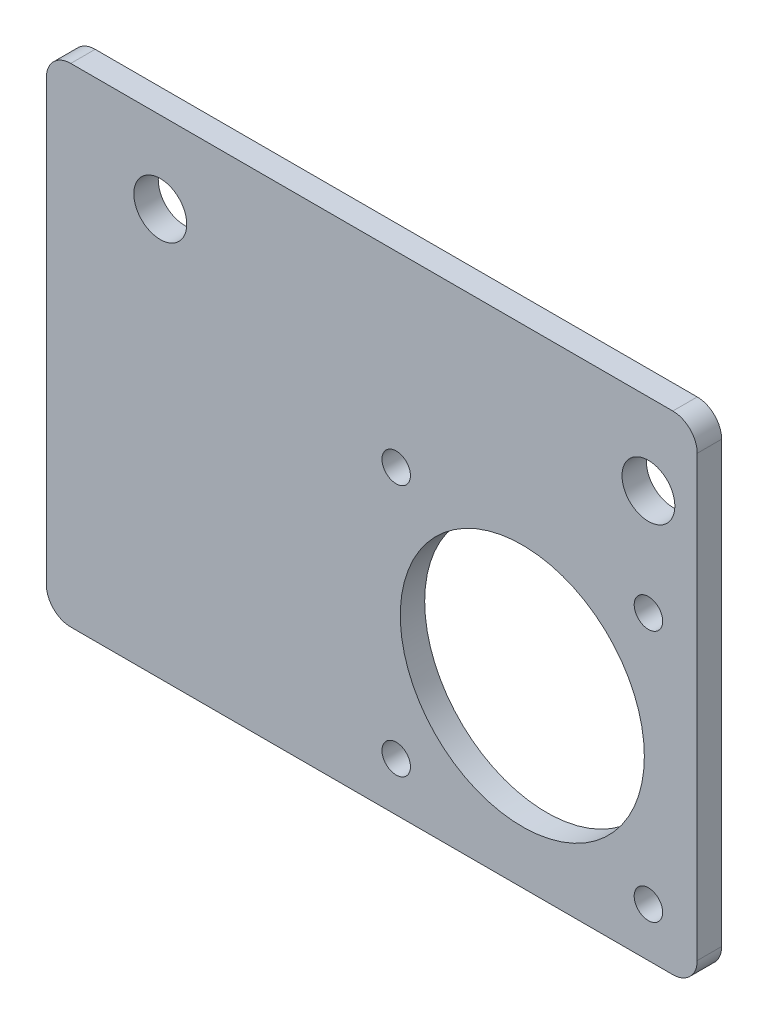
SolidWorks part; units mm, degrees
material "Alu"
ref_plane "Ebene vorne" through (0, 0, 0) normal (0, 0, 1) x (1, 0, 0)
ref_plane "Ebene oben" through (0, 0, 0) normal (0, 1, 0) x (1, 0, 0)
ref_plane "Ebene rechts" through (0, 0, 0) normal (1, 0, 0) x (0, 0, -1)
sketch "Skizze1" plane through (0, 0, 0) normal (0, 0, 1) x (1, 0, 0)
  line L1 (40, 30) -> (-40, 30)
  line L2 (40, 30) -> (40, -30)
  line L3 (40, -30) -> (-40, -30)
  line L4 (-40, 30) -> (-40, -30)
  line L5 (40, 30) -> (-40, -30) construction
  line L6 (40, -30) -> (-40, 30) construction
  point P0 (0, 0)
  dimension "D1" = 60
  dimension "D2" = 80
extrude "Aufsatz-Linear austragen1" add sketch "Skizze1" along normal blind 3
fillet "Verrundung1" radius 3 4 edges at (-40, 30, 1.5) (40, 30, 1.5) (40, -30, 1.5) (-40, -30, 1.5)
sketch "Skizze2" plane through (0, 0, 3) normal (0, 0, 1) x (1, 0, 0)
  line L0 (-26, 20) -> (34, 20) construction
  line L1 (34, 7) -> (3, 7) construction
  line L2 (34, 7) -> (34, -24) construction
  line L3 (34, -24) -> (3, -24) construction
  line L4 (3, 7) -> (3, -24) construction
  line L5 (34, 7) -> (3, -24) construction
  line L6 (34, -24) -> (3, 7) construction
  line L8 (37, 30) -> (-37, 30) construction
  line L10 (-37, -30) -> (37, -30) construction
  line L11 (40, -27) -> (40, 27) construction
  line L12 (40, 13) -> (-3, 13) construction
  line L13 (40, 13) -> (40, -30) construction
  line L14 (40, -30) -> (-3, -30) construction
  line L15 (-3, 13) -> (-3, -30) construction
  line L16 (40, 13) -> (-3, -30) construction
  line L17 (40, -30) -> (-3, 13) construction
  circle A0 centre (3, -24) radius 1.75
  circle A1 centre (3, 7) radius 1.75
  circle A2 centre (34, 7) radius 1.75
  circle A3 centre (34, -24) radius 1.75
  circle A4 centre (34, 20) radius 3.25
  circle A5 centre (-26, 20) radius 3.25
  circle A6 centre (18.5, -8.5) radius 15
  point P0 (18.5, -8.5)
  point P15 (18.5, -8.5)
  dimension "D8" = 3.5
  dimension "D9" = 6.5
  dimension "D10" = 30
  dimension "D2" = 10
  dimension "D3" = 31
  dimension "D4" = 31
  dimension "D5" = 60
  dimension "D6" = 21.5
  dimension "D7" = 43
extrude "Schnitt-Linear austragen1" cut sketch "Skizze2" against normal blind 12
